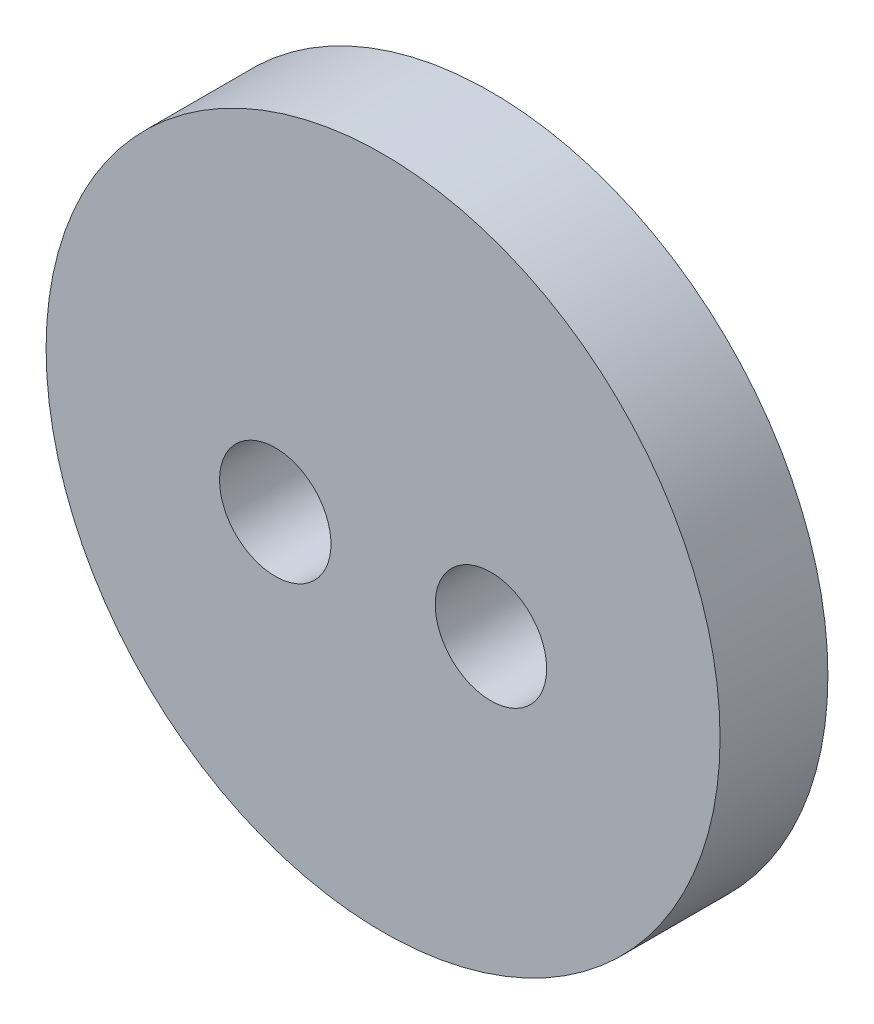
SolidWorks part; units mm, degrees
ref_plane "Front Plane" through (0, 0, 0) normal (0, 0, 1) x (1, 0, 0)
ref_plane "Top Plane" through (0, 0, 0) normal (0, 1, 0) x (1, 0, 0)
ref_plane "Right Plane" through (0, 0, 0) normal (1, 0, 0) x (0, 0, -1)
sketch "Sketch1" plane through (0, 0, 0) normal (0, 0, 1) x (1, 0, 0)
  circle A0 centre (0, 0) radius 9.375
  dimension "D1" = 18.75
extrude "Boss-Extrude1" add sketch "Sketch1" along normal blind 3
sketch "Sketch2" plane through (0, 0, 3) normal (0, 0, 1) x (1, 0, 0)
  line L0 (-12.0105, 0) -> (11.2872, 0) construction
  line L1 (0, 9.5558) -> (0, -10.038) construction
  line L2 (-12.0105, -0.75) -> (11.2872, -0.75) construction
  circle A0 centre (3, -0.75) radius 1.55
  circle A1 centre (-3, -0.75) radius 1.55
  dimension "D2" = 3.1
  dimension "D1" = 0.75
  dimension "D3" = 3
extrude "Cut-Extrude1" cut sketch "Sketch2" against normal through all
